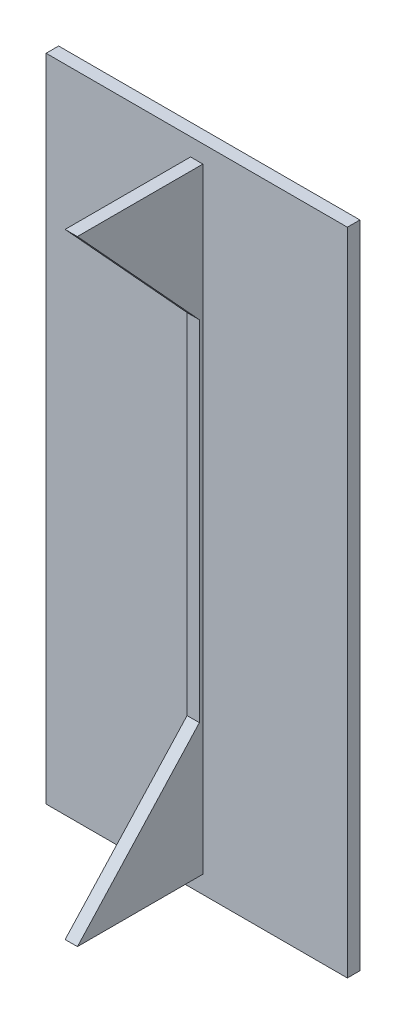
SolidWorks part; units mm, degrees
ref_plane "Přední rovina" through (0, 0, 0) normal (0, 0, 1) x (1, 0, 0)
ref_plane "Horní rovina" through (0, 0, 0) normal (0, 1, 0) x (1, 0, 0)
ref_plane "Pravá rovina" through (0, 0, 0) normal (1, 0, 0) x (0, 0, -1)
sketch "Skica1" plane through (0, 0, 0) normal (0, 0, 1) x (1, 0, 0)
  line L1 (-12, -25.9) -> (12, -25.9)
  line L2 (-12, -25.9) -> (-12, 25.9)
  line L3 (-12, 25.9) -> (12, 25.9)
  line L4 (12, -25.9) -> (12, 25.9)
  line L5 (-12, -25.9) -> (12, 25.9) construction
  line L6 (-12, 25.9) -> (12, -25.9) construction
  point P0 (0, 0)
  dimension "D1" = 24
  dimension "D2" = 51.8
extrude "Přidat vysunutím2" add sketch "Skica1" along normal blind 1
sketch "Skica2" plane through (0, 0, 1) normal (0, 0, 1) x (1, 0, 0)
  line L0 (0, 25.9) -> (0, -25.9) construction
  line L1 (12, 25.9) -> (-12, 25.9) construction
  line L2 (-12, -25.9) -> (12, -25.9) construction
  line L5 (-0.49, 25.9) -> (-0.49, -25.9)
  line L6 (-0.49, -25.9) -> (0.4901, -25.9)
  line L7 (0.4901, -25.9) -> (0.4901, 25.9)
  line L8 (-0.49, 25.9) -> (0.4901, 25.9)
  dimension "D1" = 0.9801
extrude "Přidat vysunutím3" add sketch "Skica2" along normal blind 0.28
sketch "Skica3" plane through (0, 0, 1.28) normal (0, 0, 1) x (1, 0, 0)
  line L0 (-0.49, -25.9) -> (-0.49, -13.9)
  line L1 (-0.49, 25.9) -> (-0.49, -25.9) construction
  line L2 (-0.49, -13.9) -> (0.4901, -13.9)
  line L3 (0.4901, -25.9) -> (0.4901, 25.9) construction
  line L4 (0.4901, -13.9) -> (0.4901, -25.9)
  line L5 (0.4901, -25.9) -> (-0.49, -25.9)
  line L6 (-0.49, -13.9) -> (-0.49, -25.9)
  line L7 (-0.49, 13.9) -> (-0.49, 25.9)
  line L8 (-0.49, 25.9) -> (0.4901, 25.9)
  line L9 (0.4901, 25.9) -> (0.4901, 13.9)
  line L10 (0.4901, 13.9) -> (-0.49, 13.9)
  line L11 (-0.49, 25.9) -> (-0.49, 13.9)
  line L12 (0.4901, 25.9) -> (-0.49, 25.9)
  line M1 (0.4901, 25.9) -> (-0.49, 25.9)
  line M2 (-0.49, 25.9) -> (-0.49, -25.9)
  line M3 (-0.49, -25.9) -> (0.4901, -25.9)
  line M4 (0.4901, -25.9) -> (0.4901, 25.9)
  dimension "D1" = 12
  dimension "D2" = 12
extrude "Přidat vysunutím5" add sketch "Skica3" along normal blind 11 contours L10 M4 M1 M2 | L2 M2 M3 M4
sketch "Skica6" plane through (0.4901, 0, 0) normal (1, 0, 0) x (0, 0, -1)
  line L0 (-12.28, 25.9) -> (-12.28, 13.9)
  line L1 (-12.28, 13.9) -> (-1.28, 13.9) construction
  line L2 (-12.28, 13.9) -> (-12.28, 25.9) construction
  line L3 (-12.28, 13.9) -> (-1.28, 13.9)
  line L4 (-1.28, 13.9) -> (-12.28, 25.9)
extrude "Odebrat vysunutím2" cut sketch "Skica6" against normal blind 11
sketch "Skica7" plane through (-0.49, 0, 0) normal (-1, 0, 0) x (0, 0, 1)
  line L0 (12.28, -13.9) -> (12.28, -25.9)
  line L1 (12.28, -25.9) -> (1.28, -13.9)
  line L2 (1.28, -13.9) -> (12.28, -13.9)
extrude "Odebrat vysunutím3" cut sketch "Skica7" against normal blind 11
sketch "Skica9" plane through (-0.49, 0, 0) normal (-1, 0, 0) x (0, 0, 1)
  line L1 (1, 25.9) -> (13.042, 25.9)
  line L2 (1, 25.9) -> (1, 24.5)
  line L3 (1, 24.5) -> (13.042, 24.5)
  line L4 (13.042, 25.9) -> (13.042, 24.5)
  dimension "D1" = 1.4
extrude "Odebrat vysunutím4" cut sketch "Skica9" against normal blind 11
sketch "Skica10" plane through (-0.49, 0, 0) normal (-1, 0, 0) x (0, 0, 1)
  line L0 (1, 24.5) -> (1, -25.9) construction
  line L1 (1, -25.9) -> (12.6381, -25.9)
  line L2 (1, -25.9) -> (1, -24.4954)
  line L3 (1, -24.4954) -> (12.6381, -24.4954)
  line L4 (12.6381, -25.9) -> (12.6381, -24.4954)
  line L5 (12.28, -25.9) -> (1, -25.9) construction
  dimension "D1" = 1.4046
extrude "Odebrat vysunutím5" cut sketch "Skica10" against normal blind 11
